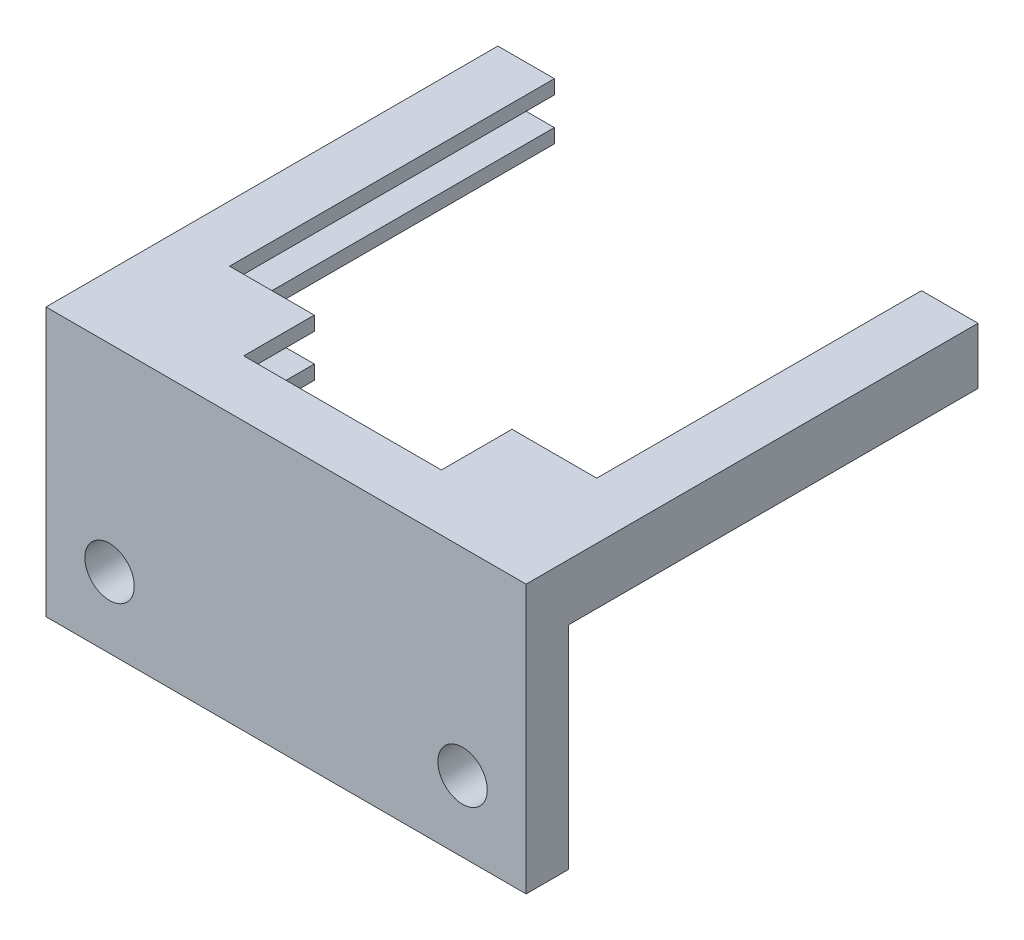
SolidWorks part; units mm, degrees
ref_plane "Front Plane" through (0, 0, 0) normal (0, 0, 1) x (1, 0, 0)
ref_plane "Top Plane" through (0, 0, 0) normal (0, 1, 0) x (1, 0, 0)
ref_plane "Right Plane" through (0, 0, 0) normal (1, 0, 0) x (0, 0, -1)
sketch "Sketch1" plane through (0, 0, 0) normal (0, 1, 0) x (1, 0, 0)
  line L1 (0, 0) -> (34, 0)
  line L2 (0, 0) -> (0, 29)
  line L3 (0, 29) -> (34, 29)
  line L4 (34, 0) -> (34, 29)
  dimension "D1" = 34
  dimension "D2" = 29
extrude "Boss-Extrude1" add sketch "Sketch1" along normal blind 4
sketch "Sketch2" plane through (0, 4, 0) normal (0, 1, 0) x (1, 0, 0)
  line L0 (34, 29) -> (0, 29) construction
  line L1 (0, 29) -> (4, 29) construction
  line L2 (4, 29) -> (30, 29)
  line L3 (4, 29) -> (4, 6)
  line L4 (4, 6) -> (30, 6)
  line L5 (30, 29) -> (30, 6)
  line L6 (30, 29) -> (34, 29) construction
  dimension "D1" = 26
  dimension "D2" = 23
extrude "Cut-Extrude1" cut sketch "Sketch2" against normal through all
sketch "Sketch3" plane through (0, 0, -29) normal (0, 0, -1) x (-1, 0, 0)
  line L0 (0, 4) -> (0, 0) construction
  line L1 (-1, 1) -> (-33, 1)
  line L2 (-1, 1) -> (-1, 3)
  line L3 (-1, 3) -> (-33, 3)
  line L4 (-33, 1) -> (-33, 3)
  line L5 (-4, 4) -> (0, 4) construction
  line L6 (-4, 0) -> (0, 0) construction
  line L7 (-34, 4) -> (-34, 0) construction
  point P6 (0, 2)
  dimension "D1" = 1
  dimension "D2" = 1
  dimension "D3" = 1
  dimension "D4" = 1
extrude "Cut-Extrude2" cut sketch "Sketch3" against normal blind 28
sketch "Sketch4" plane through (0, 0, 0) normal (-1, 0, 0) x (0, 0, 1)
  line L0 (0, 4) -> (3, 4)
  line L1 (3, 4) -> (3, -15)
  line L2 (3, -15) -> (0, -15)
  line L3 (0, -15) -> (0, 0)
  line L4 (-29, 4) -> (0, 4) construction
  line L5 (0, 0) -> (0, 4)
  dimension "D1" = 3
  dimension "D2" = 90
  dimension "D3" = 90
  dimension "D4" = 15
extrude "Boss-Extrude2" add sketch "Sketch4" against normal up to surface (34 mm away) up to face at (34, 2, -14.5)
sketch "Sketch5" plane through (0, 0, 0) normal (0, 0, -1) x (-1, 0, 0)
  line L0 (-29.5, -10) -> (-4.5, -10) construction
  line L1 (-34, -15) -> (0, -15) construction
  circle A0 centre (-29.5, -10) radius 1.75
  circle A1 centre (-4.5, -10) radius 1.75
  point P6 (-17, -15)
  point P7 (-17, -10)
  dimension "D1" = 3.5
  dimension "D2" = 25
  dimension "D3" = 5
extrude "Cut-Extrude3" cut sketch "Sketch5" against normal through all
sketch "Sketch6" plane through (0, 0, -6) normal (0, 0, -1) x (-1, 0, 0)
  line L2 (-24, 4) -> (-10, 4)
  line L3 (-24, 4) -> (-24, 0)
  line L4 (-24, 0) -> (-10, 0)
  line L5 (-10, 4) -> (-10, 0)
  line L6 (-4, 0) -> (-30, 0) construction
  line L7 (-4, 4) -> (-30, 4) construction
  point P4 (0, 0)
  point P8 (-17, 0)
  point P9 (-17, 0)
  dimension "D1" = 14
extrude "Cut-Extrude4" cut sketch "Sketch6" against normal up to surface (5 mm away) contours L5 L4 L3 L2 up to face at (17, 2, -1)
equation "\"angle\"= 0"
equation "\"D2@Sketch4\"= 90 + \"angle\""
